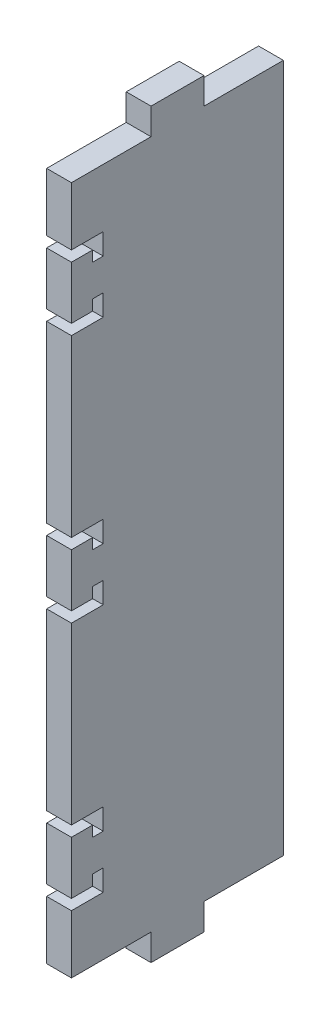
SolidWorks part; units mm, degrees
ref_plane "Front Plane" through (0, 0, 0) normal (1, 0, 0) x (0, 1, 0)
ref_plane "Top Plane" through (0, 0, 0) normal (0, 0, 1) x (0, 1, 0)
ref_plane "Right Plane" through (0, 0, 0) normal (0, 1, 0) x (-1, 0, 0)
sketch "Sketch1" plane through (0, 0, 0) normal (1, 0, 0) x (0, 1, 0)
  line L5 (-10.0816, 16.0777) -> (-6.9066, 16.0777)
  line L6 (-6.9066, 16.0777) -> (-6.9066, 25.6164)
  line L23 (-6.9066, 25.6164) -> (75.6434, 25.6164)
  line L24 (75.6434, 25.6164) -> (75.6434, 16.0777)
  line L28 (78.8184, 9.7276) -> (75.6434, 9.7276)
  line L29 (75.6434, 9.7276) -> (75.6434, 0.2162)
  line L30 (75.6434, 0.2162) -> (-6.9066, 0.2162)
  line L31 (-6.9066, 0.2162) -> (-6.9066, 9.7276)
  line L32 (-6.9066, 9.7276) -> (-10.0816, 9.7276)
  line L34 (-121.5869, 13.7666) -> (164.049, 12.5352) construction
  line L37 (75.6434, 16.0777) -> (78.8184, 16.0777)
  line L38 (78.8184, 16.0777) -> (78.8184, 9.7276)
  line L39 (-10.0816, 16.0777) -> (-10.0816, 9.7276)
  dimension "D1" = 3.175
  dimension "D2" = 3.175
  dimension "D3" = 3.175
  dimension "D4" = 12.7
  dimension "D5" = 12.7
  dimension "D6" = 3.175
  dimension "D7" = 88.9
extrude "Boss-Extrude1" add sketch "Sketch1" along normal blind 2.9718
sketch "Sketch2" plane through (2.9718, 0, 0) normal (1, 0, 0) x (0, 1, 0)
  line L0 (34.3684, 25.6164) -> (34.3684, 0.2162) construction
  line L1 (75.6434, 25.6164) -> (-6.9066, 25.6164) construction
  line L2 (-6.9066, 0.2162) -> (75.6434, 0.2162) construction
  line L28 (0.0784, 25.6164) -> (1.3484, 25.6164)
  line L29 (1.3484, 25.6164) -> (1.3484, 23.0764)
  line L30 (1.3484, 23.0764) -> (2.6184, 23.0764)
  line L31 (2.6184, 23.0764) -> (2.6184, 21.8064)
  line L32 (0.0784, 25.6164) -> (0.0784, 21.8064)
  line L33 (0.0784, 21.8064) -> (2.6184, 21.8064)
  line L34 (6.4284, 23.0764) -> (6.4284, 21.8064)
  line L35 (6.4284, 21.8064) -> (8.9684, 21.8064)
  line L36 (8.9684, 21.8064) -> (8.9684, 25.6164)
  line L37 (8.9684, 25.6164) -> (7.6984, 25.6164)
  line L38 (7.6984, 25.6164) -> (7.6984, 23.0764)
  line L39 (7.6984, 23.0764) -> (6.4284, 23.0764)
  line L64 (29.9234, 25.6164) -> (31.1934, 25.6164)
  line L65 (31.1934, 25.6164) -> (31.1934, 23.0764)
  line L66 (31.1934, 23.0764) -> (32.4634, 23.0764)
  line L67 (32.4634, 23.0764) -> (32.4634, 21.8064)
  line L68 (29.9234, 25.6164) -> (29.9234, 21.8064)
  line L69 (29.9234, 21.8064) -> (32.4634, 21.8064)
  line L70 (36.2734, 23.0764) -> (36.2734, 21.8064)
  line L71 (36.2734, 21.8064) -> (38.8134, 21.8064)
  line L72 (38.8134, 21.8064) -> (38.8134, 25.6164)
  line L73 (38.8134, 25.6164) -> (37.5434, 25.6164)
  line L74 (37.5434, 25.6164) -> (37.5434, 23.0764)
  line L75 (37.5434, 23.0764) -> (36.2734, 23.0764)
  line L89 (59.7684, 25.6164) -> (61.0384, 25.6164)
  line L90 (61.0384, 25.6164) -> (61.0384, 23.0764)
  line L91 (61.0384, 23.0764) -> (62.3084, 23.0764)
  line L92 (62.3084, 23.0764) -> (62.3084, 21.8064)
  line L93 (59.7684, 25.6164) -> (59.7684, 21.8064)
  line L94 (59.7684, 21.8064) -> (62.3084, 21.8064)
  line L95 (66.1184, 23.0764) -> (66.1184, 21.8064)
  line L96 (66.1184, 21.8064) -> (68.6584, 21.8064)
  line L97 (68.6584, 21.8064) -> (68.6584, 25.6164)
  line L98 (68.6584, 25.6164) -> (67.3884, 25.6164)
  line L99 (67.3884, 25.6164) -> (67.3884, 23.0764)
  line L100 (67.3884, 23.0764) -> (66.1184, 23.0764)
  point P30 (1.3484, 21.8064)
  point P31 (7.6984, 21.8064)
  point P32 (61.0384, 21.8064)
  point P33 (67.3884, 21.8064)
  dimension "D1" = 6.35
  dimension "D2" = 2.54
  dimension "D3" = 3.81
  dimension "D4" = 2.54
  dimension "D5" = 2.54
  dimension "D6" = 8.89
  dimension "D7" = 2.54
  dimension "D8" = 3.81
  dimension "D9" = 2.54
  dimension "D10" = 2.54
  dimension "D11" = 8.89
  dimension "D12" = 25.4
  dimension "D13" = 25.4
  dimension "D15" = 6.35
  dimension "D16" = 2.54
  dimension "D17" = 3.81
  dimension "D18" = 2.54
  dimension "D19" = 2.54
  dimension "D20" = 8.89
extrude "Cut-Extrude1" cut sketch "Sketch2" against normal through all
